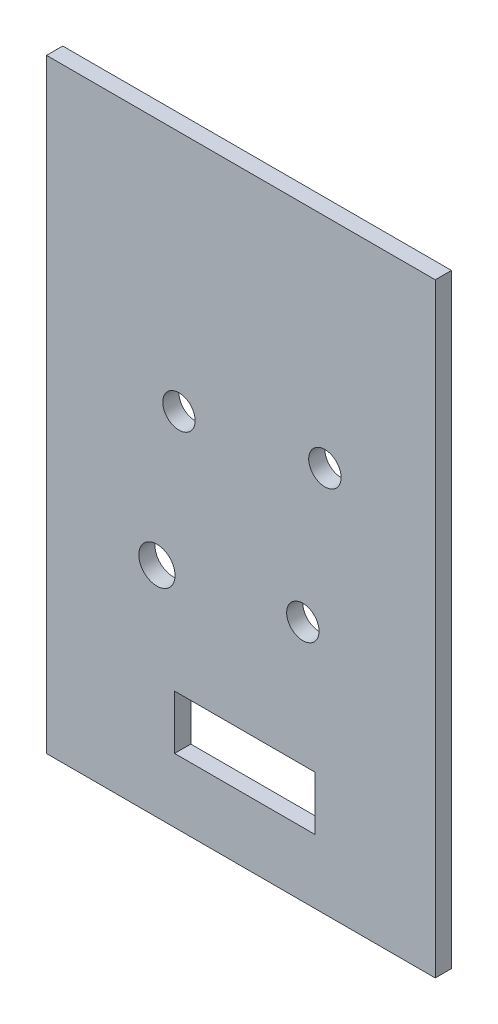
SolidWorks part; units mm, degrees
ref_plane "Front Plane" through (0, 0, 0) normal (0, 0, 1) x (1, 0, 0)
ref_plane "Top Plane" through (0, 0, 0) normal (0, 1, 0) x (1, 0, 0)
ref_plane "Right Plane" through (0, 0, 0) normal (1, 0, 0) x (0, 0, -1)
sketch "Sketch1" plane through (0, 0, 0) normal (0, 0, 1) x (1, 0, 0)
  line L5 (-6.1415, -17.0593) -> (6.8585, -17.0593)
  line L10 (-6.1415, -17.0593) -> (-6.1415, -22.0593)
  line L15 (-6.1415, -22.0593) -> (6.8585, -22.0593)
  line L16 (6.8585, -17.0593) -> (6.8585, -22.0593)
  line L17 (-18, 0) -> (-18, 28)
  line L18 (-18, 28) -> (18, 28)
  line L19 (18, 28) -> (18, -28)
  line L20 (-18, 0) -> (-18, -28)
  line L21 (-18, -28) -> (18, -28)
  circle A0 centre (7.7782, 7.7782) radius 1.5
  circle A1 centre (-5.738, 5.5745) radius 1.5
  circle A2 centre (-7.7782, -7.7782) radius 1.6804
  circle A3 centre (5.738, -5.5745) radius 1.5
  point P11 (-23.9169, 6.0384)
  point P13 (-23.9169, 6.0384)
extrude "Boss-Extrude3" add sketch "Sketch1" along normal blind 1.5
